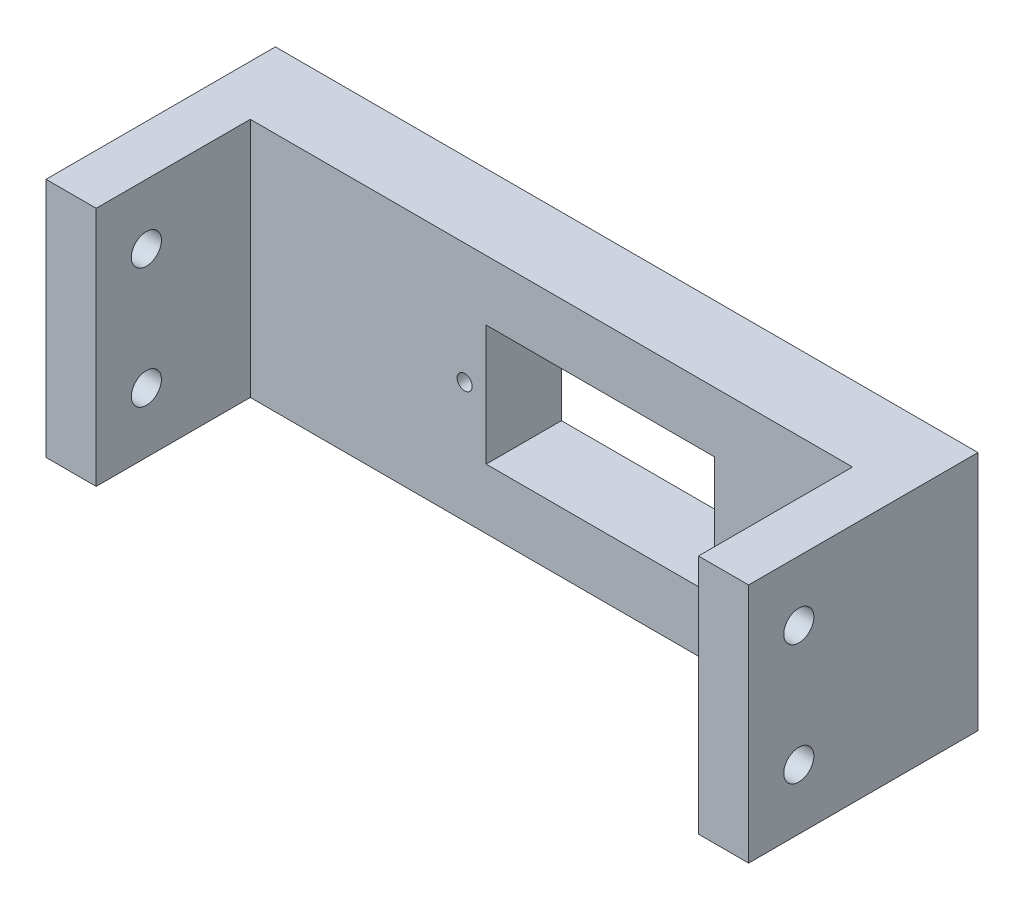
SolidWorks part; units mm, degrees
ref_plane "Front Plane" through (0, 0, 0) normal (0, 0, 1) x (1, 0, 0)
ref_plane "Top Plane" through (0, 0, 0) normal (0, 1, 0) x (1, 0, 0)
ref_plane "Right Plane" through (0, 0, 0) normal (1, 0, 0) x (0, 0, -1)
sketch "Sketch1" plane through (0, 0, 0) normal (0, 1, 0) x (1, 0, 0)
  line L0 (-30, -3.75) -> (-30, -19.1)
  line L1 (-35, 3.75) -> (35, 3.75)
  line L2 (0, 3.75) -> (0, -3.75) construction
  line L3 (-35, -3.75) -> (35, -3.75)
  line L4 (35, 3.75) -> (35, -3.75)
  line L5 (35, -3.75) -> (30, -3.75)
  line L6 (35, -3.75) -> (35, -19.1)
  line L7 (35, -19.1) -> (30, -19.1)
  line L8 (30, -3.75) -> (30, -19.1)
  line L9 (-35, -19.1) -> (-30, -19.1)
  line L10 (-35, -3.75) -> (-35, -19.1)
  line L11 (-35, -3.75) -> (-30, -3.75)
  line L12 (-35, 3.75) -> (-35, -3.75)
  point P7 (0, 0)
  dimension "D1" = 35
  dimension "D2" = 22.85
  dimension "D3" = 7.5
  dimension "D4" = 5
extrude "Boss-Extrude1" add sketch "Sketch1" along normal blind 24 contours L3 L10 L9 L0 | L2 L1 L12 L3 | L1 L2 L3 L4 | L3 L8 L7 L6
sketch "Sketch2" plane through (-35, 0, 0) normal (-1, 0, 0) x (0, 0, 1)
  line L0 (-3.75, 24) -> (19.1, 24) construction
  line L1 (19.1, 24) -> (19.1, 0) construction
  circle A0 centre (14.1, 18) radius 1.5
  circle A1 centre (14.1, 6) radius 1.5
  dimension "D2" = 3
  dimension "D3" = 12
  dimension "D1" = 5
  dimension "D4" = 6
extrude "Cut-Extrude1" cut sketch "Sketch2" against normal through all
sketch "Sketch8" plane through (0, 0, -3.75) normal (0, 0, -1) x (-1, 0, 0)
  line L0 (0, 12) -> (35, 12) construction
  line L1 (35, 24) -> (35, 0) construction
  line L2 (0, 12) -> (0, 24) construction
  line L3 (35, 24) -> (-35, 24) construction
  line L5 (6.5, 18) -> (-16.25, 18)
  line L6 (6.5, 18) -> (6.5, 6)
  line L7 (6.5, 6) -> (-16.25, 6)
  line L8 (-16.25, 18) -> (-16.25, 6)
  point P0 (0, 12)
  point P12 (6.5, 12)
  dimension "D1" = 6.5
  dimension "D2" = 22.75
  dimension "D3" = 12
extrude "Cut-Extrude4" cut sketch "Sketch8" against normal up to next
sketch "Sketch9" plane through (0, 0, -3.75) normal (0, 0, -1) x (-1, 0, 0)
  line L0 (-35, 24) -> (-35, 0) construction
  line L1 (-19.16, 12) -> (-35, 12) construction
  circle A0 centre (-19.16, 12) radius 0.75
  circle A1 centre (8.64, 12) radius 0.75
  dimension "D3" = 1.5
  dimension "D1" = 27.8
  dimension "D2" = 15.84
extrude "Cut-Extrude5" cut sketch "Sketch9" against normal through all
